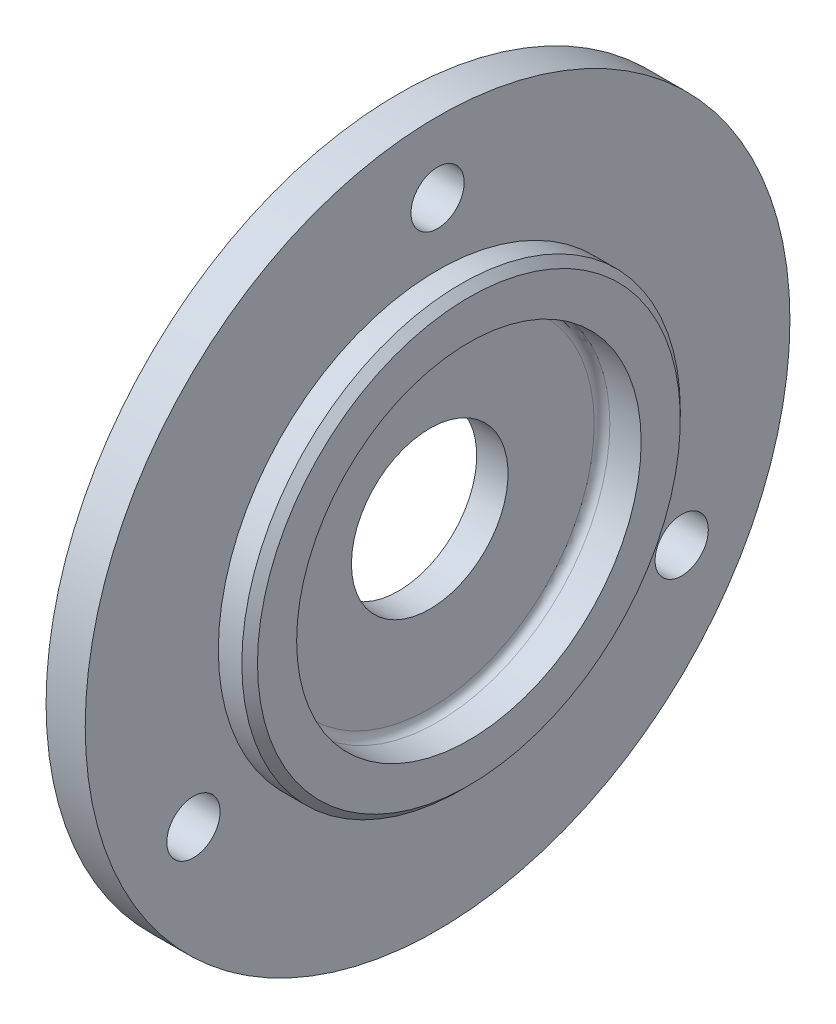
SolidWorks part; units mm, degrees
material "Alliage 1060"
ref_plane "Plan de face" through (0, 0, 0) normal (0, 0, 1) x (1, 0, 0)
ref_plane "Plan de dessus" through (0, 0, 0) normal (0, 1, 0) x (1, 0, 0)
ref_plane "Plan de droite" through (0, 0, 0) normal (1, 0, 0) x (0, 0, -1)
sketch "Esquisse1" plane through (0, 0, 0) normal (0, 0, 1) x (1, 0, 0)
  line L0 (-14.7778, 0) -> (22.3469, 0) construction
  line L1 (-0.5, 5) -> (-0.5, 10.5)
  line L2 (0, 11) -> (2, 11)
  line L3 (2, 11) -> (2, 13.5)
  line L4 (1.5, 14) -> (0, 14)
  line L5 (0, 14) -> (0, 22.5)
  line L6 (0, 22.5) -> (-2.5, 22.5)
  line L7 (-2.5, 22.5) -> (-2.5, 5)
  line L8 (-2.5, 5) -> (-0.5, 5)
  line L9 (2, 13.5) -> (1.5, 14)
  arc A0 (-0.5, 10.5) -> (0, 11) centre (0, 10.5) cw
  point P7 (2, 14)
  dimension "D8" = 0.5
  dimension "D1" = 10
  dimension "D2" = 28
  dimension "D3" = 22
  dimension "D4" = 45
  dimension "D5" = 2.5
  dimension "D6" = 2
  dimension "D7" = 2
revolve "Révolution1" add sketch "Esquisse1" angle 360 about L0
sketch "Esquisse2" plane through (0, 0, 0) normal (1, 0, 0) x (0, 0, -1)
  circle A0 centre (0, 18) radius 1.7
  circle A1 centre (15.5885, -9) radius 1.7
  circle A2 centre (-15.5885, -9) radius 1.7
  dimension "D1" = 3.4
  dimension "D2" = 18
extrude "Enlèv. mat.-Extru.1" cut sketch "Esquisse2" against normal blind 10
